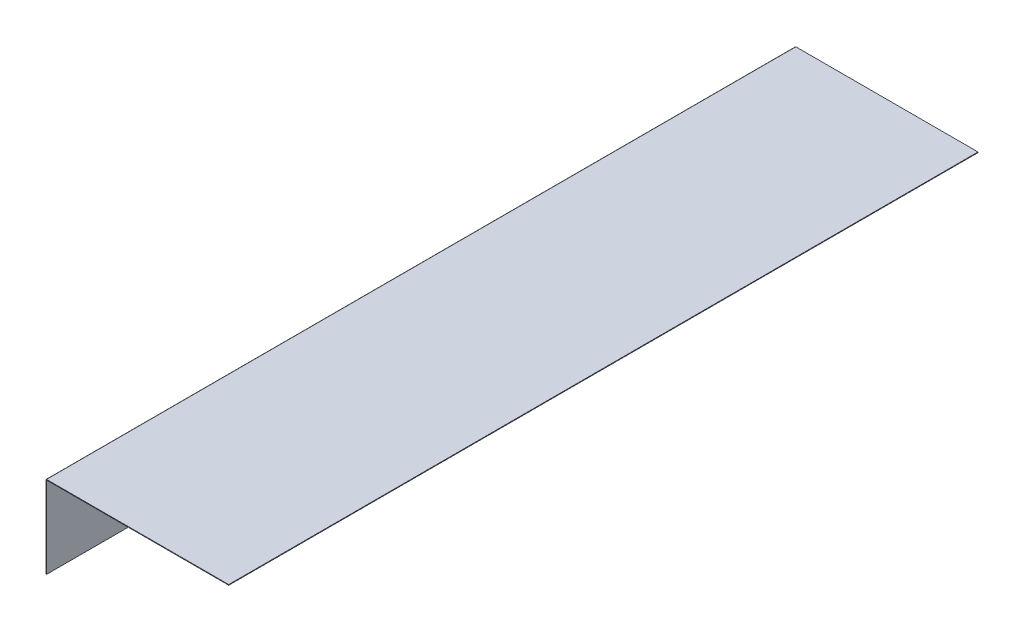
SolidWorks part; units mm, degrees
ref_plane "Front Plane" through (0, 0, 0) normal (0, 0, 1) x (1, 0, 0)
ref_plane "Top Plane" through (0, 0, 0) normal (0, 1, 0) x (1, 0, 0)
ref_plane "Right Plane" through (0, 0, 0) normal (1, 0, 0) x (0, 0, -1)
sketch "Sketch1" plane through (0, 0, 0) normal (0, 0, 1) x (1, 0, 0)
  line L0 (0, 0) -> (0, 135)
  line L1 (0, 135) -> (300, 135)
  line L2 (300, 135) -> (300, 134)
  line L3 (300, 134) -> (1, 134)
  line L4 (1, 134) -> (1, 0)
  line L5 (1, 0) -> (0, 0)
  dimension "D1" = 1
  dimension "D2" = 1
  dimension "D3" = 300
  dimension "D4" = 135
extrude "Boss-Extrude1" add sketch "Sketch1" along normal blind 1230
fillet "Fillet1" radius 1 2 edges at (0, 135, 615) (1, 134, 615)
